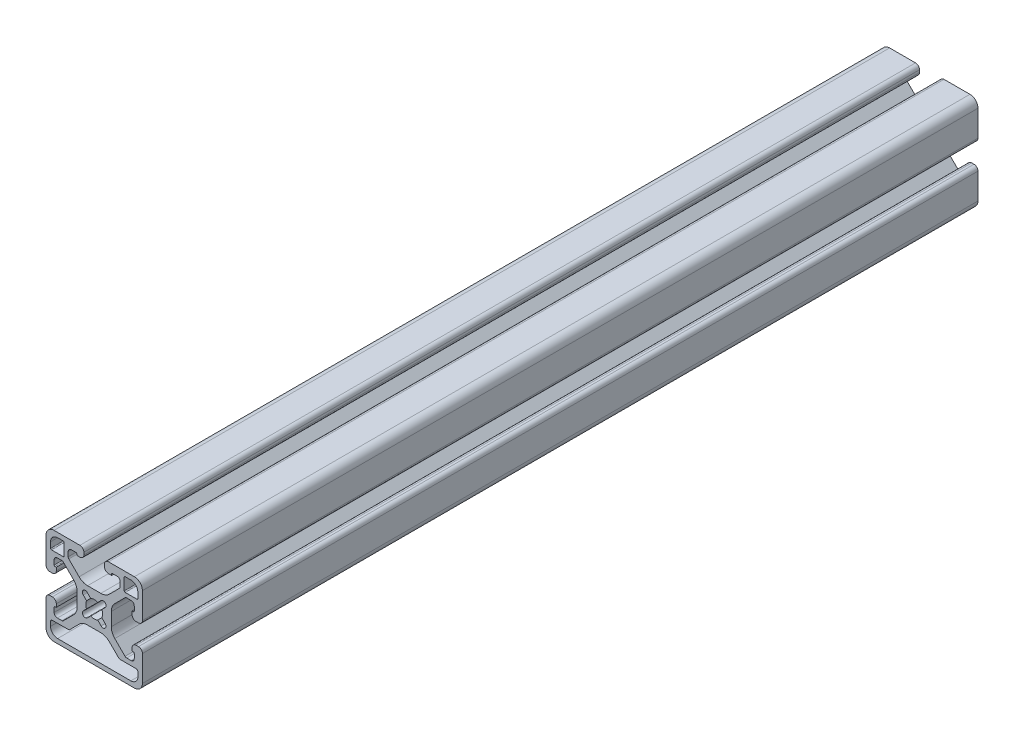
SolidWorks part; units mm, degrees
material "6105-T5 Aluminum"
ref_plane "Front Plane" through (0, 0, 0) normal (0, 0, 1) x (1, 0, 0)
ref_plane "Top Plane" through (0, 0, 0) normal (0, 1, 0) x (1, 0, 0)
ref_plane "Right Plane" through (0, 0, 0) normal (1, 0, 0) x (0, 0, -1)
sketch "Sketch1" plane through (0, 0, 0) normal (0, 0, 1) x (1, 0, 0)
  line L0 (-2.6153, -6.738) -> (2.6153, -6.738)
  line L1 (5.9739, -8.1292) -> (9.6866, -11.8418)
  line L2 (10.2254, -12.065) -> (16.51, -12.065)
  line L3 (17.272, -12.827) -> (17.272, -14.478)
  line L4 (14.478, -17.272) -> (-14.478, -17.272)
  line L5 (-17.272, -14.478) -> (-17.272, -12.827)
  line L6 (-16.51, -12.065) -> (-10.2254, -12.065)
  line L7 (-9.6866, -11.8418) -> (-5.9739, -8.1292)
  line L8 (16.8656, 11.8618) -> (12.2428, 11.8618)
  line L9 (11.8618, 12.2428) -> (11.8618, 16.8656)
  line L10 (12.2428, 17.2466) -> (14.4526, 17.2466)
  line L11 (17.2466, 14.4526) -> (17.2466, 12.2428)
  line L12 (-11.8618, 16.8656) -> (-11.8618, 12.2428)
  line L13 (-12.2428, 11.8618) -> (-16.8656, 11.8618)
  line L14 (-17.2466, 12.2428) -> (-17.2466, 14.4526)
  line L15 (-14.4526, 17.2466) -> (-12.2428, 17.2466)
  line L16 (1.4014, 3.0179) -> (2.7224, 4.3388)
  line L17 (4.3388, 2.7224) -> (3.0179, 1.4014)
  line L18 (3.0179, -1.4014) -> (4.3388, -2.7224)
  line L19 (2.7224, -4.3388) -> (1.4014, -3.0179)
  line L20 (-1.4014, -3.0179) -> (-2.7224, -4.3388)
  line L21 (-4.3388, -2.7224) -> (-3.0179, -1.4014)
  line L22 (-3.0179, 1.4014) -> (-4.3388, 2.7224)
  line L23 (-2.7224, 4.3388) -> (-1.4014, 3.0179)
  line L24 (-15.8242, 7.239) -> (-15.8242, 9.017)
  line L25 (-14.5542, 10.287) -> (-12.8105, 10.287)
  line L26 (-12.1819, 10.0266) -> (-8.1292, 5.9739)
  line L27 (-6.738, 2.6153) -> (-6.738, -2.6153)
  line L28 (-8.1292, -5.9739) -> (-12.1819, -10.0266)
  line L29 (-12.8105, -10.287) -> (-14.5542, -10.287)
  line L30 (-15.8242, -9.017) -> (-15.8242, -7.239)
  line L31 (-15.4432, -6.858) -> (-14.986, -6.858)
  line L32 (-14.986, -6.858) -> (-14.986, -5.6388)
  line L33 (-16.5608, -4.064) -> (-17.4752, -4.064)
  line L34 (-19.05, -5.6388) -> (-19.05, -15.875)
  line L35 (-15.875, -19.05) -> (15.875, -19.05)
  line L36 (19.05, -15.875) -> (19.05, -5.6388)
  line L37 (17.4752, -4.064) -> (16.5608, -4.064)
  line L38 (14.986, -5.6388) -> (14.986, -6.858)
  line L39 (14.986, -6.858) -> (15.4432, -6.858)
  line L40 (15.8242, -7.239) -> (15.8242, -9.017)
  line L41 (14.5542, -10.287) -> (12.8105, -10.287)
  line L42 (12.1819, -10.0266) -> (8.1292, -5.9739)
  line L43 (6.738, -2.6153) -> (6.738, 2.6153)
  line L44 (8.1292, 5.9739) -> (12.1819, 10.0266)
  line L45 (12.8105, 10.287) -> (14.5542, 10.287)
  line L46 (15.8242, 9.017) -> (15.8242, 7.239)
  line L47 (15.4432, 6.858) -> (14.986, 6.858)
  line L48 (14.986, 6.858) -> (14.986, 5.6388)
  line L49 (16.5608, 4.064) -> (17.4752, 4.064)
  line L50 (19.05, 5.6388) -> (19.05, 15.875)
  line L51 (15.875, 19.05) -> (5.6388, 19.05)
  line L52 (4.064, 17.4752) -> (4.064, 16.5608)
  line L53 (5.6388, 14.986) -> (6.858, 14.986)
  line L54 (6.858, 14.986) -> (6.858, 15.4432)
  line L55 (7.239, 15.8242) -> (9.017, 15.8242)
  line L56 (10.287, 14.5542) -> (10.287, 12.8105)
  line L57 (10.0266, 12.1819) -> (5.9739, 8.1292)
  line L58 (2.6153, 6.738) -> (-2.6153, 6.738)
  line L59 (-5.9739, 8.1292) -> (-10.0266, 12.1819)
  line L60 (-10.287, 12.8105) -> (-10.287, 14.5542)
  line L61 (-9.017, 15.8242) -> (-7.239, 15.8242)
  line L62 (-6.858, 15.4432) -> (-6.858, 14.986)
  line L63 (-6.858, 14.986) -> (-5.6388, 14.986)
  line L64 (-4.064, 16.5608) -> (-4.064, 17.4752)
  line L65 (-5.6388, 19.05) -> (-15.875, 19.05)
  line L66 (-19.05, 15.875) -> (-19.05, 5.6388)
  line L67 (-17.4752, 4.064) -> (-16.5608, 4.064)
  line L68 (-14.986, 5.6388) -> (-14.986, 6.858)
  line L69 (-14.986, 6.858) -> (-15.4432, 6.858)
  arc A0 (-2.6153, -6.738) -> (-5.9739, -8.1292) centre (-2.6153, -11.4878) ccw
  arc A1 (5.9739, -8.1292) -> (2.6153, -6.738) centre (2.6153, -11.4878) ccw
  arc A2 (9.6866, -11.8418) -> (10.2254, -12.065) centre (10.2254, -11.303) ccw
  arc A3 (17.272, -12.827) -> (16.51, -12.065) centre (16.51, -12.827) ccw
  arc A4 (14.478, -17.272) -> (17.272, -14.478) centre (14.478, -14.478) ccw
  arc A5 (-17.272, -14.478) -> (-14.478, -17.272) centre (-14.478, -14.478) ccw
  arc A6 (-16.51, -12.065) -> (-17.272, -12.827) centre (-16.51, -12.827) ccw
  arc A7 (-10.2254, -12.065) -> (-9.6866, -11.8418) centre (-10.2254, -11.303) ccw
  arc A8 (11.8618, 12.2428) -> (12.2428, 11.8618) centre (12.2428, 12.2428) ccw
  arc A9 (12.2428, 17.2466) -> (11.8618, 16.8656) centre (12.2428, 16.8656) ccw
  arc A10 (17.2466, 14.4526) -> (14.4526, 17.2466) centre (14.4526, 14.4526) ccw
  arc A11 (16.8656, 11.8618) -> (17.2466, 12.2428) centre (16.8656, 12.2428) ccw
  arc A12 (-12.2428, 11.8618) -> (-11.8618, 12.2428) centre (-12.2428, 12.2428) ccw
  arc A13 (-17.2466, 12.2428) -> (-16.8656, 11.8618) centre (-16.8656, 12.2428) ccw
  arc A14 (-14.4526, 17.2466) -> (-17.2466, 14.4526) centre (-14.4526, 14.4526) ccw
  arc A15 (-11.8618, 16.8656) -> (-12.2428, 17.2466) centre (-12.2428, 16.8656) ccw
  arc A16 (1.4014, 3.0179) -> (-1.4014, 3.0179) centre (0, 0) ccw
  arc A17 (4.3388, 2.7224) -> (2.7224, 4.3388) centre (3.5306, 3.5306) ccw
  arc A18 (3.0179, -1.4014) -> (3.0179, 1.4014) centre (0, 0) ccw
  arc A19 (2.7224, -4.3388) -> (4.3388, -2.7224) centre (3.5306, -3.5306) ccw
  arc A20 (-1.4014, -3.0179) -> (1.4014, -3.0179) centre (0, 0) ccw
  arc A21 (-4.3388, -2.7224) -> (-2.7224, -4.3388) centre (-3.5306, -3.5306) ccw
  arc A22 (-3.0179, 1.4014) -> (-3.0179, -1.4014) centre (0, 0) ccw
  arc A23 (-2.7224, 4.3388) -> (-4.3388, 2.7224) centre (-3.5306, 3.5306) ccw
  arc A24 (-15.8242, 7.239) -> (-15.4432, 6.858) centre (-15.4432, 7.239) ccw
  arc A25 (-14.5542, 10.287) -> (-15.8242, 9.017) centre (-14.5542, 9.017) ccw
  arc A26 (-12.1819, 10.0266) -> (-12.8105, 10.287) centre (-12.8105, 9.398) ccw
  arc A27 (-6.738, 2.6153) -> (-8.1292, 5.9739) centre (-11.4878, 2.6153) ccw
  arc A28 (-8.1292, -5.9739) -> (-6.738, -2.6153) centre (-11.4878, -2.6153) ccw
  arc A29 (-12.8105, -10.287) -> (-12.1819, -10.0266) centre (-12.8105, -9.398) ccw
  arc A30 (-15.8242, -9.017) -> (-14.5542, -10.287) centre (-14.5542, -9.017) ccw
  arc A31 (-15.4432, -6.858) -> (-15.8242, -7.239) centre (-15.4432, -7.239) ccw
  arc A32 (-14.986, -5.6388) -> (-16.5608, -4.064) centre (-16.5608, -5.6388) ccw
  arc A33 (-17.4752, -4.064) -> (-19.05, -5.6388) centre (-17.4752, -5.6388) ccw
  arc A34 (-19.05, -15.875) -> (-15.875, -19.05) centre (-15.875, -15.875) ccw
  arc A35 (15.875, -19.05) -> (19.05, -15.875) centre (15.875, -15.875) ccw
  arc A36 (19.05, -5.6388) -> (17.4752, -4.064) centre (17.4752, -5.6388) ccw
  arc A37 (16.5608, -4.064) -> (14.986, -5.6388) centre (16.5608, -5.6388) ccw
  arc A38 (15.8242, -7.239) -> (15.4432, -6.858) centre (15.4432, -7.239) ccw
  arc A39 (14.5542, -10.287) -> (15.8242, -9.017) centre (14.5542, -9.017) ccw
  arc A40 (12.1819, -10.0266) -> (12.8105, -10.287) centre (12.8105, -9.398) ccw
  arc A41 (6.738, -2.6153) -> (8.1292, -5.9739) centre (11.4878, -2.6153) ccw
  arc A42 (8.1292, 5.9739) -> (6.738, 2.6153) centre (11.4878, 2.6153) ccw
  arc A43 (12.8105, 10.287) -> (12.1819, 10.0266) centre (12.8105, 9.398) ccw
  arc A44 (15.8242, 9.017) -> (14.5542, 10.287) centre (14.5542, 9.017) ccw
  arc A45 (15.4432, 6.858) -> (15.8242, 7.239) centre (15.4432, 7.239) ccw
  arc A46 (14.986, 5.6388) -> (16.5608, 4.064) centre (16.5608, 5.6388) ccw
  arc A47 (17.4752, 4.064) -> (19.05, 5.6388) centre (17.4752, 5.6388) ccw
  arc A48 (19.05, 15.875) -> (15.875, 19.05) centre (15.875, 15.875) ccw
  arc A49 (5.6388, 19.05) -> (4.064, 17.4752) centre (5.6388, 17.4752) ccw
  arc A50 (4.064, 16.5608) -> (5.6388, 14.986) centre (5.6388, 16.5608) ccw
  arc A51 (7.239, 15.8242) -> (6.858, 15.4432) centre (7.239, 15.4432) ccw
  arc A52 (10.287, 14.5542) -> (9.017, 15.8242) centre (9.017, 14.5542) ccw
  arc A53 (10.0266, 12.1819) -> (10.287, 12.8105) centre (9.398, 12.8105) ccw
  arc A54 (2.6153, 6.738) -> (5.9739, 8.1292) centre (2.6153, 11.4878) ccw
  arc A55 (-5.9739, 8.1292) -> (-2.6153, 6.738) centre (-2.6153, 11.4878) ccw
  arc A56 (-10.287, 12.8105) -> (-10.0266, 12.1819) centre (-9.398, 12.8105) ccw
  arc A57 (-9.017, 15.8242) -> (-10.287, 14.5542) centre (-9.017, 14.5542) ccw
  arc A58 (-6.858, 15.4432) -> (-7.239, 15.8242) centre (-7.239, 15.4432) ccw
  arc A59 (-5.6388, 14.986) -> (-4.064, 16.5608) centre (-5.6388, 16.5608) ccw
  arc A60 (-4.064, 17.4752) -> (-5.6388, 19.05) centre (-5.6388, 17.4752) ccw
  arc A61 (-15.875, 19.05) -> (-19.05, 15.875) centre (-15.875, 15.875) ccw
  arc A62 (-19.05, 5.6388) -> (-17.4752, 4.064) centre (-17.4752, 5.6388) ccw
  arc A63 (-16.5608, 4.064) -> (-14.986, 5.6388) centre (-16.5608, 5.6388) ccw
extrude "Extrude1" add sketch "Sketch1" against normal mid plane 330.2
hole_wizard "7060-LEFT" positions "Sketch3" profile "Sketch2" tap size "5/16-18" standard "Ansi Inch"
sketch "Sketch3" plane through (0, 0, 165.1) normal (0, 0, 1) x (1, 0, 0)
  point P1 (0, 0)
sketch "Sketch2" plane through (0, 0, 165.1) normal (1, 0, 0) x (0, -1, 0)
  line L0 (0, 0) -> (0, 22.1161)
  line L1 (0, 22.1161) -> (3.3274, 20.1168)
  line L2 (3.3274, 20.1168) -> (3.3274, 0)
  line L5 (3.3274, 0) -> (0, 0)
  line L10 (0, 22.1161) -> (-3.3274, 20.1168) construction
  line L11 (0, -6.35) -> (0, 107.95) construction
  dimension "Tap Drill Dia." = 6.6548
  dimension "Tap Drill Depth" = 20.1168
  dimension "Drill Angle" = 118
hole_wizard "7060-RIGHT" positions "Sketch5" profile "Sketch4" tap size "5/16-18" standard "Ansi Inch"
sketch "Sketch5" plane through (0, 0, -165.1) normal (0, 0, -1) x (-1, 0, 0)
  point P1 (0, 0)
sketch "Sketch4" plane through (0, 0, -165.1) normal (1, 0, 0) x (0, 1, 0)
  line L0 (0, 0) -> (0, 22.1161)
  line L1 (0, 22.1161) -> (3.3274, 20.1168)
  line L2 (3.3274, 20.1168) -> (3.3274, 0)
  line L5 (3.3274, 0) -> (0, 0)
  line L10 (0, 22.1161) -> (-3.3274, 20.1168) construction
  line L11 (0, -6.35) -> (0, 107.95) construction
  dimension "Tap Drill Dia." = 6.6548
  dimension "Tap Drill Depth" = 20.1168
  dimension "Drill Angle" = 118
